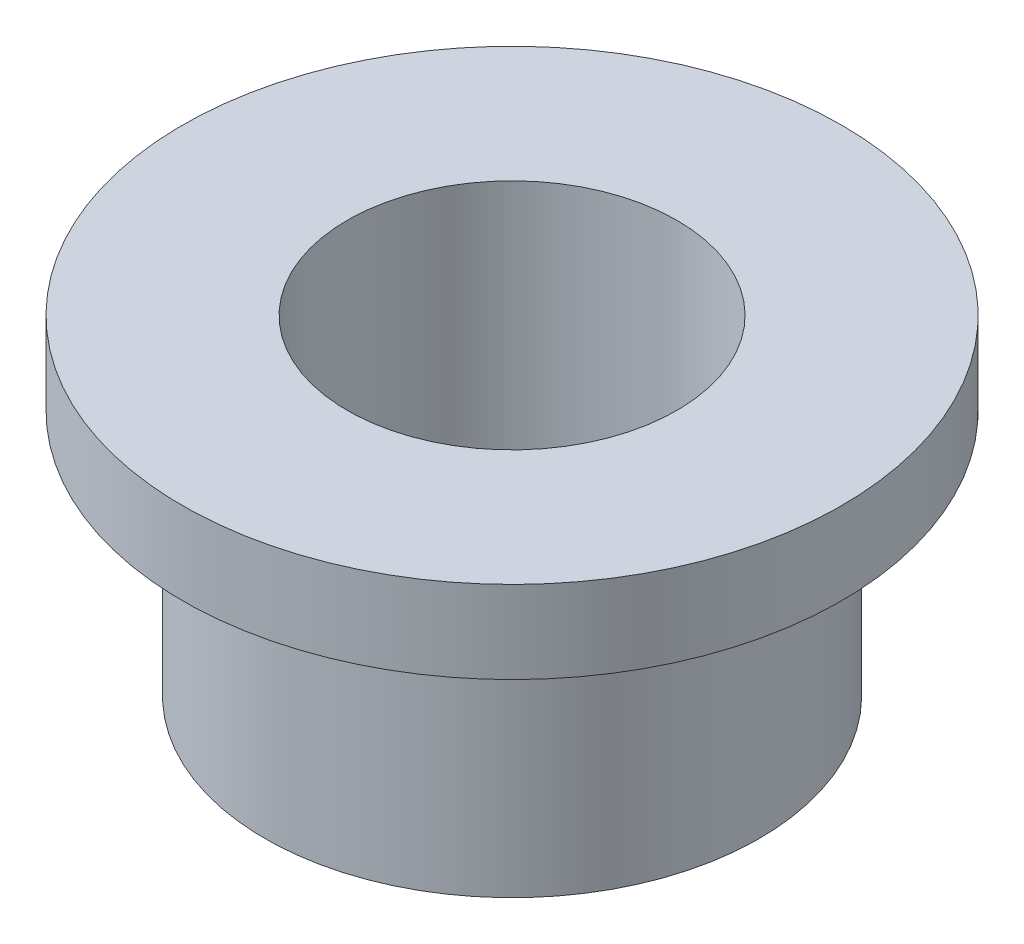
SolidWorks part; units mm, degrees
ref_plane "Front Plane" through (0, 0, 0) normal (0, 0, 1) x (1, 0, 0)
ref_plane "Top Plane" through (0, 0, 0) normal (0, 1, 0) x (1, 0, 0)
ref_plane "Right Plane" through (0, 0, 0) normal (1, 0, 0) x (0, 0, -1)
sketch "Sketch1" plane through (0, 0, 0) normal (0, 0, 1) x (1, 0, 0)
  line L0 (0, 0) -> (0, 13.6347) construction
  line L1 (1, 0) -> (1, 2)
  line L2 (1, 2) -> (2, 2)
  dimension "D1" = 2
  dimension "D2" = 2
  dimension "D3" = 4
revolve "Revolve-Thin1" add sketch "Sketch1" angle 360 about L0
